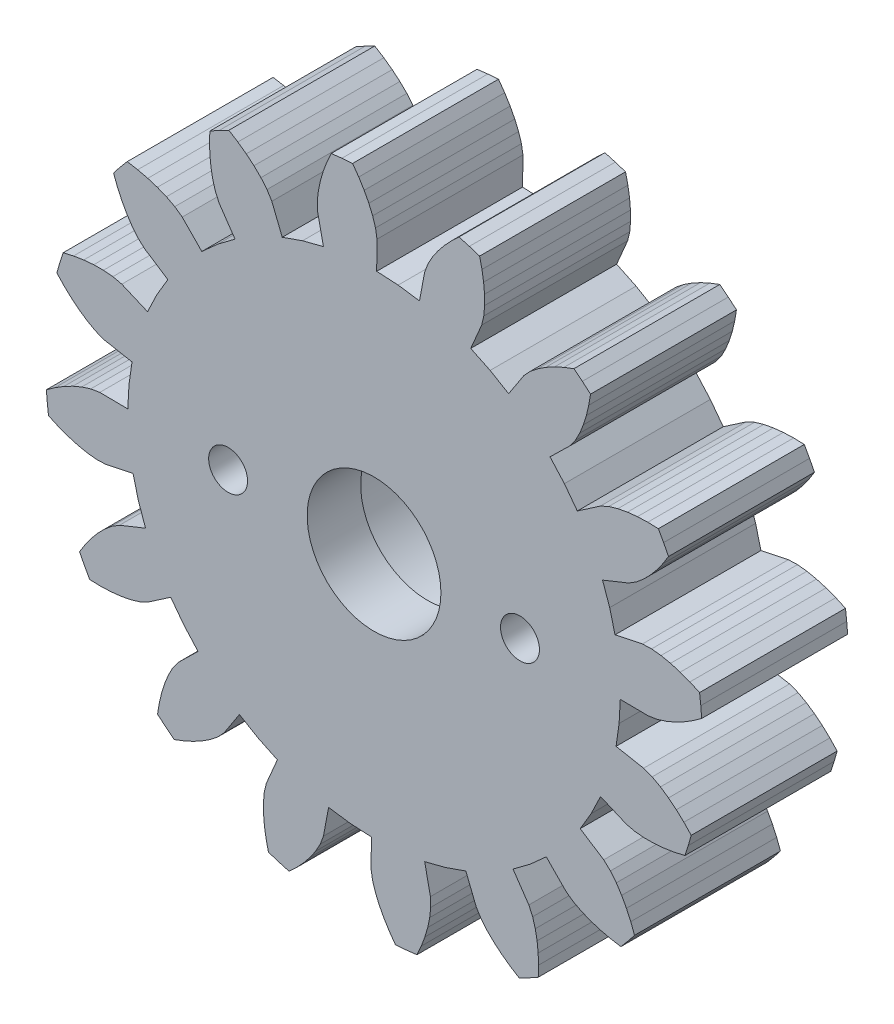
SolidWorks part; units mm, degrees
ref_plane "Front Plane" through (0, 0, 0) normal (0, 0, 1) x (1, 0, 0)
ref_plane "Top Plane" through (0, 0, 0) normal (0, 1, 0) x (1, 0, 0)
ref_plane "Right Plane" through (0, 0, 0) normal (1, 0, 0) x (0, 0, -1)
sketch "Sketch1" plane through (0, 0, 0) normal (0, 0, 1) x (1, 0, 0)
  line L0 (0.1087, 10.1244) -> (0.1211, 11.2757)
  line L1 (0.1211, 11.2757) -> (0.0606, 11.6468)
  line L2 (0.0606, 11.6468) -> (-0.0565, 12.0174)
  line L3 (-0.0565, 12.0174) -> (-0.2135, 12.3863)
  line L4 (-0.2135, 12.3863) -> (-0.4052, 12.7523)
  line L5 (-0.4052, 12.7523) -> (-0.6285, 13.1143)
  line L6 (-0.6285, 13.1143) -> (-0.8817, 13.4712)
  line L7 (-0.8817, 13.4712) -> (-1.3232, 13.435)
  line L8 (-1.3232, 13.435) -> (-1.7633, 13.3843)
  line L9 (-1.7633, 13.3843) -> (-1.942, 12.985)
  line L10 (-1.942, 12.985) -> (-2.0905, 12.5863)
  line L11 (-2.0905, 12.5863) -> (-2.207, 12.19)
  line L12 (-2.207, 12.19) -> (-2.2891, 11.7975)
  line L13 (-2.2891, 11.7975) -> (-2.3316, 11.4112)
  line L14 (-2.3316, 11.4112) -> (-2.3185, 11.0354)
  line L15 (-2.3185, 11.0354) -> (-2.0818, 9.9087)
  line L16 (-2.0818, 9.9087) -> (-2.9391, 9.689)
  line L17 (-2.9391, 9.689) -> (-3.774, 9.3953)
  line L18 (-3.774, 9.3953) -> (-4.2031, 10.4637)
  line L19 (-4.2031, 10.4637) -> (-4.4011, 10.7834)
  line L20 (-4.4011, 10.7834) -> (-4.6511, 11.081)
  line L21 (-4.6511, 11.081) -> (-4.9373, 11.3617)
  line L22 (-4.9373, 11.3617) -> (-5.2544, 11.6266)
  line L23 (-5.2544, 11.6266) -> (-5.5993, 11.8755)
  line L24 (-5.5993, 11.8755) -> (-5.9698, 12.1083)
  line L25 (-5.9698, 12.1083) -> (-6.3639, 11.9059)
  line L26 (-6.3639, 11.9059) -> (-6.7511, 11.6907)
  line L27 (-6.7511, 11.6907) -> (-6.7633, 11.2534)
  line L28 (-6.7633, 11.2534) -> (-6.7479, 10.8283)
  line L29 (-6.7479, 10.8283) -> (-6.7039, 10.4175)
  line L30 (-6.7039, 10.4175) -> (-6.6295, 10.0235)
  line L31 (-6.6295, 10.0235) -> (-6.521, 9.6503)
  line L32 (-6.521, 9.6503) -> (-6.3651, 9.3081)
  line L33 (-6.3651, 9.3081) -> (-5.7152, 8.3577)
  line L34 (-5.7152, 8.3577) -> (-6.4232, 7.8267)
  line L35 (-6.4232, 7.8267) -> (-7.0822, 7.2359)
  line L36 (-7.0822, 7.2359) -> (-7.8875, 8.0587)
  line L37 (-7.8875, 8.0587) -> (-8.1927, 8.2783)
  line L38 (-8.1927, 8.2783) -> (-8.5375, 8.4576)
  line L39 (-8.5375, 8.4576) -> (-8.9094, 8.6074)
  line L40 (-8.9094, 8.6074) -> (-9.3038, 8.7308)
  line L41 (-9.3038, 8.7308) -> (-9.7177, 8.8288)
  line L42 (-9.7177, 8.8288) -> (-10.149, 8.9021)
  line L43 (-10.149, 8.9021) -> (-10.4356, 8.5643)
  line L44 (-10.4356, 8.5643) -> (-10.711, 8.2173)
  line L45 (-10.711, 8.2173) -> (-10.555, 7.8085)
  line L46 (-10.555, 7.8085) -> (-10.3781, 7.4217)
  line L47 (-10.3781, 7.4217) -> (-10.1802, 7.059)
  line L48 (-10.1802, 7.059) -> (-9.9607, 6.7235)
  line L49 (-9.9607, 6.7235) -> (-9.7176, 6.4202)
  line L50 (-9.7176, 6.4202) -> (-9.4426, 6.1637)
  line L51 (-9.4426, 6.1637) -> (-8.4785, 5.5344)
  line L52 (-8.4785, 5.5344) -> (-8.9295, 4.7729)
  line L53 (-8.9295, 4.7729) -> (-9.3121, 3.9749)
  line L54 (-9.3121, 3.9749) -> (-10.371, 4.4269)
  line L55 (-10.371, 4.4269) -> (-10.737, 4.513)
  line L56 (-10.737, 4.513) -> (-11.1243, 4.5467)
  line L57 (-11.1243, 4.5467) -> (-11.5252, 4.5427)
  line L58 (-11.5252, 4.5427) -> (-11.9367, 4.5058)
  line L59 (-11.9367, 4.5058) -> (-12.3566, 4.438)
  line L60 (-12.3566, 4.438) -> (-12.7832, 4.3406)
  line L61 (-12.7832, 4.3406) -> (-12.9187, 3.9188)
  line L62 (-12.9187, 3.9188) -> (-13.0403, 3.4929)
  line L63 (-13.0403, 3.4929) -> (-12.7397, 3.1749)
  line L64 (-12.7397, 3.1749) -> (-12.4283, 2.8853)
  line L65 (-12.4283, 2.8853) -> (-12.1067, 2.6259)
  line L66 (-12.1067, 2.6259) -> (-11.7755, 2.3999)
  line L67 (-11.7755, 2.3999) -> (-11.4348, 2.2128)
  line L68 (-11.4348, 2.2128) -> (-11.0826, 2.081)
  line L69 (-11.0826, 2.081) -> (-9.9511, 1.8685)
  line L70 (-9.9511, 1.8685) -> (-10.0762, 0.9924)
  line L71 (-10.0762, 0.9924) -> (-10.1244, 0.1087)
  line L72 (-10.1244, 0.1087) -> (-11.2757, 0.1211)
  line L73 (-11.2757, 0.1211) -> (-11.6468, 0.0606)
  line L74 (-11.6468, 0.0606) -> (-12.0174, -0.0565)
  line L75 (-12.0174, -0.0565) -> (-12.3863, -0.2135)
  line L76 (-12.3863, -0.2135) -> (-12.7523, -0.4052)
  line L77 (-12.7523, -0.4052) -> (-13.1143, -0.6285)
  line L78 (-13.1143, -0.6285) -> (-13.4712, -0.8817)
  line L79 (-13.4712, -0.8817) -> (-13.435, -1.3232)
  line L80 (-13.435, -1.3232) -> (-13.3843, -1.7633)
  line L81 (-13.3843, -1.7633) -> (-12.985, -1.942)
  line L82 (-12.985, -1.942) -> (-12.5863, -2.0905)
  line L83 (-12.5863, -2.0905) -> (-12.19, -2.207)
  line L84 (-12.19, -2.207) -> (-11.7975, -2.2891)
  line L85 (-11.7975, -2.2891) -> (-11.4112, -2.3316)
  line L86 (-11.4112, -2.3316) -> (-11.0354, -2.3185)
  line L87 (-11.0354, -2.3185) -> (-9.9087, -2.0818)
  line L88 (-9.9087, -2.0818) -> (-9.689, -2.9391)
  line L89 (-9.689, -2.9391) -> (-9.3953, -3.774)
  line L90 (-9.3953, -3.774) -> (-10.4637, -4.2031)
  line L91 (-10.4637, -4.2031) -> (-10.7834, -4.4011)
  line L92 (-10.7834, -4.4011) -> (-11.081, -4.6511)
  line L93 (-11.081, -4.6511) -> (-11.3617, -4.9373)
  line L94 (-11.3617, -4.9373) -> (-11.6266, -5.2544)
  line L95 (-11.6266, -5.2544) -> (-11.8755, -5.5993)
  line L96 (-11.8755, -5.5993) -> (-12.1083, -5.9698)
  line L97 (-12.1083, -5.9698) -> (-11.9059, -6.3639)
  line L98 (-11.9059, -6.3639) -> (-11.6907, -6.7511)
  line L99 (-11.6907, -6.7511) -> (-11.2534, -6.7633)
  line L100 (-11.2534, -6.7633) -> (-10.8283, -6.7479)
  line L101 (-10.8283, -6.7479) -> (-10.4175, -6.7039)
  line L102 (-10.4175, -6.7039) -> (-10.0235, -6.6295)
  line L103 (-10.0235, -6.6295) -> (-9.6503, -6.521)
  line L104 (-9.6503, -6.521) -> (-9.3081, -6.3651)
  line L105 (-9.3081, -6.3651) -> (-8.3577, -5.7152)
  line L106 (-8.3577, -5.7152) -> (-7.8267, -6.4232)
  line L107 (-7.8267, -6.4232) -> (-7.2359, -7.0822)
  line L108 (-7.2359, -7.0822) -> (-8.0587, -7.8875)
  line L109 (-8.0587, -7.8875) -> (-8.2783, -8.1927)
  line L110 (-8.2783, -8.1927) -> (-8.4576, -8.5375)
  line L111 (-8.4576, -8.5375) -> (-8.6074, -8.9094)
  line L112 (-8.6074, -8.9094) -> (-8.7308, -9.3038)
  line L113 (-8.7308, -9.3038) -> (-8.8288, -9.7177)
  line L114 (-8.8288, -9.7177) -> (-8.9021, -10.149)
  line L115 (-8.9021, -10.149) -> (-8.5643, -10.4356)
  line L116 (-8.5643, -10.4356) -> (-8.2173, -10.711)
  line L117 (-8.2173, -10.711) -> (-7.8085, -10.555)
  line L118 (-7.8085, -10.555) -> (-7.4217, -10.3781)
  line L119 (-7.4217, -10.3781) -> (-7.059, -10.1802)
  line L120 (-7.059, -10.1802) -> (-6.7235, -9.9607)
  line L121 (-6.7235, -9.9607) -> (-6.4202, -9.7176)
  line L122 (-6.4202, -9.7176) -> (-6.1637, -9.4426)
  line L123 (-6.1637, -9.4426) -> (-5.5344, -8.4785)
  line L124 (-5.5344, -8.4785) -> (-4.7729, -8.9295)
  line L125 (-4.7729, -8.9295) -> (-3.9749, -9.3121)
  line L126 (-3.9749, -9.3121) -> (-4.4269, -10.371)
  line L127 (-4.4269, -10.371) -> (-4.513, -10.737)
  line L128 (-4.513, -10.737) -> (-4.5467, -11.1243)
  line L129 (-4.5467, -11.1243) -> (-4.5427, -11.5252)
  line L130 (-4.5427, -11.5252) -> (-4.5058, -11.9367)
  line L131 (-4.5058, -11.9367) -> (-4.438, -12.3566)
  line L132 (-4.438, -12.3566) -> (-4.3406, -12.7832)
  line L133 (-4.3406, -12.7832) -> (-3.9188, -12.9187)
  line L134 (-3.9188, -12.9187) -> (-3.4929, -13.0403)
  line L135 (-3.4929, -13.0403) -> (-3.1749, -12.7397)
  line L136 (-3.1749, -12.7397) -> (-2.8853, -12.4283)
  line L137 (-2.8853, -12.4283) -> (-2.6259, -12.1067)
  line L138 (-2.6259, -12.1067) -> (-2.3999, -11.7755)
  line L139 (-2.3999, -11.7755) -> (-2.2128, -11.4348)
  line L140 (-2.2128, -11.4348) -> (-2.081, -11.0826)
  line L141 (-2.081, -11.0826) -> (-1.8685, -9.9511)
  line L142 (-1.8685, -9.9511) -> (-0.9924, -10.0762)
  line L143 (-0.9924, -10.0762) -> (-0.1087, -10.1244)
  line L144 (-0.1087, -10.1244) -> (-0.1211, -11.2757)
  line L145 (-0.1211, -11.2757) -> (-0.0606, -11.6468)
  line L146 (-0.0606, -11.6468) -> (0.0565, -12.0174)
  line L147 (0.0565, -12.0174) -> (0.2135, -12.3863)
  line L148 (0.2135, -12.3863) -> (0.4052, -12.7523)
  line L149 (0.4052, -12.7523) -> (0.6285, -13.1143)
  line L150 (0.6285, -13.1143) -> (0.8817, -13.4712)
  line L151 (0.8817, -13.4712) -> (1.3232, -13.435)
  line L152 (1.3232, -13.435) -> (1.7633, -13.3843)
  line L153 (1.7633, -13.3843) -> (1.942, -12.985)
  line L154 (1.942, -12.985) -> (2.0905, -12.5863)
  line L155 (2.0905, -12.5863) -> (2.207, -12.19)
  line L156 (2.207, -12.19) -> (2.2891, -11.7975)
  line L157 (2.2891, -11.7975) -> (2.3316, -11.4112)
  line L158 (2.3316, -11.4112) -> (2.3185, -11.0354)
  line L159 (2.3185, -11.0354) -> (2.0818, -9.9087)
  line L160 (2.0818, -9.9087) -> (2.9391, -9.689)
  line L161 (2.9391, -9.689) -> (3.774, -9.3953)
  line L162 (3.774, -9.3953) -> (4.2031, -10.4637)
  line L163 (4.2031, -10.4637) -> (4.4011, -10.7834)
  line L164 (4.4011, -10.7834) -> (4.6511, -11.081)
  line L165 (4.6511, -11.081) -> (4.9373, -11.3617)
  line L166 (4.9373, -11.3617) -> (5.2544, -11.6266)
  line L167 (5.2544, -11.6266) -> (5.5993, -11.8755)
  line L168 (5.5993, -11.8755) -> (5.9698, -12.1083)
  line L169 (5.9698, -12.1083) -> (6.3639, -11.9059)
  line L170 (6.3639, -11.9059) -> (6.7511, -11.6907)
  line L171 (6.7511, -11.6907) -> (6.7633, -11.2534)
  line L172 (6.7633, -11.2534) -> (6.7479, -10.8283)
  line L173 (6.7479, -10.8283) -> (6.7039, -10.4175)
  line L174 (6.7039, -10.4175) -> (6.6295, -10.0235)
  line L175 (6.6295, -10.0235) -> (6.521, -9.6503)
  line L176 (6.521, -9.6503) -> (6.3651, -9.3081)
  line L177 (6.3651, -9.3081) -> (5.7152, -8.3577)
  line L178 (5.7152, -8.3577) -> (6.4232, -7.8267)
  line L179 (6.4232, -7.8267) -> (7.0822, -7.2359)
  line L180 (7.0822, -7.2359) -> (7.8875, -8.0587)
  line L181 (7.8875, -8.0587) -> (8.1927, -8.2783)
  line L182 (8.1927, -8.2783) -> (8.5375, -8.4576)
  line L183 (8.5375, -8.4576) -> (8.9094, -8.6074)
  line L184 (8.9094, -8.6074) -> (9.3038, -8.7308)
  line L185 (9.3038, -8.7308) -> (9.7177, -8.8288)
  line L186 (9.7177, -8.8288) -> (10.149, -8.9021)
  line L187 (10.149, -8.9021) -> (10.4356, -8.5643)
  line L188 (10.4356, -8.5643) -> (10.711, -8.2173)
  line L189 (10.711, -8.2173) -> (10.555, -7.8085)
  line L190 (10.555, -7.8085) -> (10.3781, -7.4217)
  line L191 (10.3781, -7.4217) -> (10.1802, -7.059)
  line L192 (10.1802, -7.059) -> (9.9607, -6.7235)
  line L193 (9.9607, -6.7235) -> (9.7176, -6.4202)
  line L194 (9.7176, -6.4202) -> (9.4426, -6.1637)
  line L195 (9.4426, -6.1637) -> (8.4785, -5.5344)
  line L196 (8.4785, -5.5344) -> (8.9295, -4.7729)
  line L197 (8.9295, -4.7729) -> (9.3121, -3.9749)
  line L198 (9.3121, -3.9749) -> (10.371, -4.4269)
  line L199 (10.371, -4.4269) -> (10.737, -4.513)
  line L200 (10.737, -4.513) -> (11.1243, -4.5467)
  line L201 (11.1243, -4.5467) -> (11.5252, -4.5427)
  line L202 (11.5252, -4.5427) -> (11.9367, -4.5058)
  line L203 (11.9367, -4.5058) -> (12.3566, -4.438)
  line L204 (12.3566, -4.438) -> (12.7832, -4.3406)
  line L205 (12.7832, -4.3406) -> (12.9187, -3.9188)
  line L206 (12.9187, -3.9188) -> (13.0403, -3.4929)
  line L207 (13.0403, -3.4929) -> (12.7397, -3.1749)
  line L208 (12.7397, -3.1749) -> (12.4283, -2.8853)
  line L209 (12.4283, -2.8853) -> (12.1067, -2.6259)
  line L210 (12.1067, -2.6259) -> (11.7755, -2.3999)
  line L211 (11.7755, -2.3999) -> (11.4348, -2.2128)
  line L212 (11.4348, -2.2128) -> (11.0826, -2.081)
  line L213 (11.0826, -2.081) -> (9.9511, -1.8685)
  line L214 (9.9511, -1.8685) -> (10.0762, -0.9924)
  line L215 (10.0762, -0.9924) -> (10.1244, -0.1087)
  line L216 (10.1244, -0.1087) -> (11.2757, -0.1211)
  line L217 (11.2757, -0.1211) -> (11.6468, -0.0606)
  line L218 (11.6468, -0.0606) -> (12.0174, 0.0565)
  line L219 (12.0174, 0.0565) -> (12.3863, 0.2135)
  line L220 (12.3863, 0.2135) -> (12.7523, 0.4052)
  line L221 (12.7523, 0.4052) -> (13.1143, 0.6285)
  line L222 (13.1143, 0.6285) -> (13.4712, 0.8817)
  line L223 (13.4712, 0.8817) -> (13.435, 1.3232)
  line L224 (13.435, 1.3232) -> (13.3843, 1.7633)
  line L225 (13.3843, 1.7633) -> (12.985, 1.942)
  line L226 (12.985, 1.942) -> (12.5863, 2.0905)
  line L227 (12.5863, 2.0905) -> (12.19, 2.207)
  line L228 (12.19, 2.207) -> (11.7975, 2.2891)
  line L229 (11.7975, 2.2891) -> (11.4112, 2.3316)
  line L230 (11.4112, 2.3316) -> (11.0354, 2.3185)
  line L231 (11.0354, 2.3185) -> (9.9087, 2.0818)
  line L232 (9.9087, 2.0818) -> (9.689, 2.9391)
  line L233 (9.689, 2.9391) -> (9.3953, 3.774)
  line L234 (9.3953, 3.774) -> (10.4637, 4.2031)
  line L235 (10.4637, 4.2031) -> (10.7834, 4.4011)
  line L236 (10.7834, 4.4011) -> (11.081, 4.6511)
  line L237 (11.081, 4.6511) -> (11.3617, 4.9373)
  line L238 (11.3617, 4.9373) -> (11.6266, 5.2544)
  line L239 (11.6266, 5.2544) -> (11.8755, 5.5993)
  line L240 (11.8755, 5.5993) -> (12.1083, 5.9698)
  line L241 (12.1083, 5.9698) -> (11.9059, 6.3639)
  line L242 (11.9059, 6.3639) -> (11.6907, 6.7511)
  line L243 (11.6907, 6.7511) -> (11.2534, 6.7633)
  line L244 (11.2534, 6.7633) -> (10.8283, 6.7479)
  line L245 (10.8283, 6.7479) -> (10.4175, 6.7039)
  line L246 (10.4175, 6.7039) -> (10.0235, 6.6295)
  line L247 (10.0235, 6.6295) -> (9.6503, 6.521)
  line L248 (9.6503, 6.521) -> (9.3081, 6.3651)
  line L249 (9.3081, 6.3651) -> (8.3577, 5.7152)
  line L250 (8.3577, 5.7152) -> (7.8267, 6.4232)
  line L251 (7.8267, 6.4232) -> (7.2359, 7.0822)
  line L252 (7.2359, 7.0822) -> (8.0587, 7.8875)
  line L253 (8.0587, 7.8875) -> (8.2783, 8.1927)
  line L254 (8.2783, 8.1927) -> (8.4576, 8.5375)
  line L255 (8.4576, 8.5375) -> (8.6074, 8.9094)
  line L256 (8.6074, 8.9094) -> (8.7308, 9.3038)
  line L257 (8.7308, 9.3038) -> (8.8288, 9.7177)
  line L258 (8.8288, 9.7177) -> (8.9021, 10.149)
  line L259 (8.9021, 10.149) -> (8.5643, 10.4356)
  line L260 (8.5643, 10.4356) -> (8.2173, 10.711)
  line L261 (8.2173, 10.711) -> (7.8085, 10.555)
  line L262 (7.8085, 10.555) -> (7.4217, 10.3781)
  line L263 (7.4217, 10.3781) -> (7.059, 10.1802)
  line L264 (7.059, 10.1802) -> (6.7235, 9.9607)
  line L265 (6.7235, 9.9607) -> (6.4202, 9.7176)
  line L266 (6.4202, 9.7176) -> (6.1637, 9.4426)
  line L267 (6.1637, 9.4426) -> (5.5344, 8.4785)
  line L268 (5.5344, 8.4785) -> (4.7729, 8.9295)
  line L269 (4.7729, 8.9295) -> (3.9749, 9.3121)
  line L270 (3.9749, 9.3121) -> (4.4269, 10.371)
  line L271 (4.4269, 10.371) -> (4.513, 10.737)
  line L272 (4.513, 10.737) -> (4.5467, 11.1243)
  line L273 (4.5467, 11.1243) -> (4.5427, 11.5252)
  line L274 (4.5427, 11.5252) -> (4.5058, 11.9367)
  line L275 (4.5058, 11.9367) -> (4.438, 12.3566)
  line L276 (4.438, 12.3566) -> (4.3406, 12.7832)
  line L277 (4.3406, 12.7832) -> (3.9188, 12.9187)
  line L278 (3.9188, 12.9187) -> (3.4929, 13.0403)
  line L279 (3.4929, 13.0403) -> (3.1749, 12.7397)
  line L280 (3.1749, 12.7397) -> (2.8853, 12.4283)
  line L281 (2.8853, 12.4283) -> (2.6259, 12.1067)
  line L282 (2.6259, 12.1067) -> (2.3999, 11.7755)
  line L283 (2.3999, 11.7755) -> (2.2128, 11.4348)
  line L284 (2.2128, 11.4348) -> (2.081, 11.0826)
  line L285 (2.081, 11.0826) -> (1.8685, 9.9511)
  line L286 (1.8685, 9.9511) -> (0.9924, 10.0762)
  line L287 (0.9924, 10.0762) -> (0.1087, 10.1244)
extrude "Boss-Extrude1" add sketch "Sketch1" along normal blind 6 from offset 14
sketch "Sketch2" plane through (0, 0, 0) normal (0, 0, 1) x (1, 0, 0)
  circle A0 centre (0, 0) radius 2.75
extrude "Cut-Extrude1" cut sketch "Sketch2" against normal through all and the other way through all
sketch "Sketch3" plane through (0, 0, 0) normal (0, 0, 1) x (1, 0, 0)
  circle A0 centre (0, 0) radius 3.8
extrude "Cut-Extrude2" cut sketch "Sketch3" along normal blind 3.8 from offset 14
sketch "Sketch4" plane through (0, 0, 0) normal (0, 0, 1) x (1, 0, 0)
  circle A0 centre (6, 0) radius 0.8
  circle A1 centre (-6, 0) radius 0.8
extrude "Cut-Extrude3" cut sketch "Sketch4" against normal through all and the other way through all
